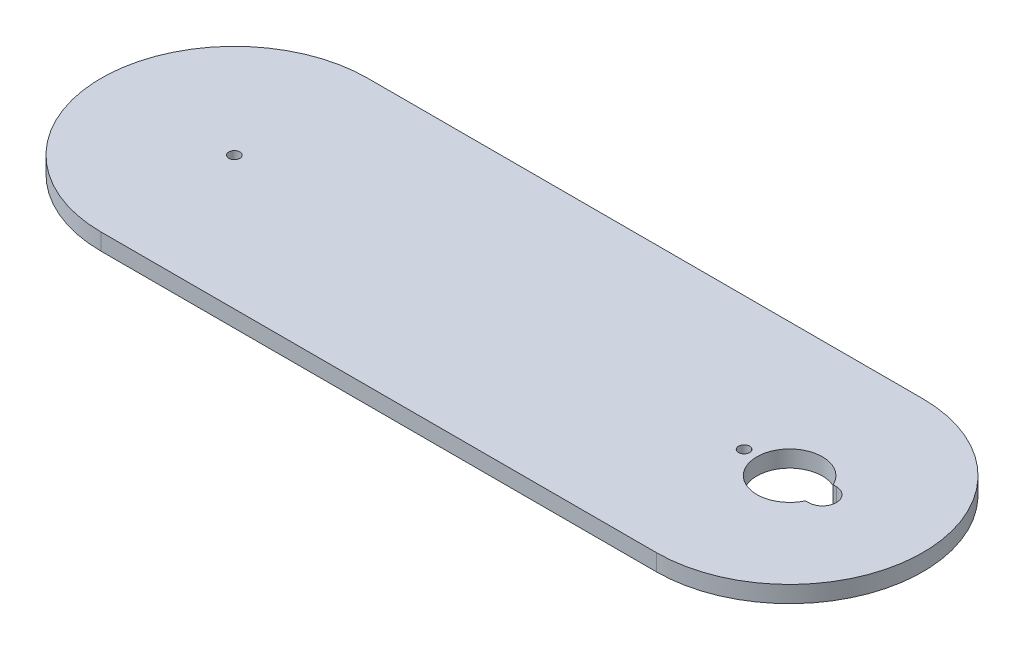
SolidWorks part; units mm, degrees
ref_plane "Front Plane" through (0, 0, 0) normal (0, 0, 1) x (1, 0, 0)
ref_plane "Top Plane" through (0, 0, 0) normal (0, 1, 0) x (1, 0, 0)
ref_plane "Right Plane" through (0, 0, 0) normal (1, 0, 0) x (0, 0, -1)
sketch "Sketch1" plane through (0, 0, 0) normal (0, 1, 0) x (1, 0, 0)
  line L0 (0, 24) -> (100, 24)
  line L2 (100, -24) -> (0, -24)
  arc A0 (0, 24) -> (0, -24) centre (0, 0) ccw
  arc A1 (100, 24) -> (100, -24) centre (100, 0) cw
  dimension "D1" = 48
  dimension "D4" = 24
  dimension "D2" = 48
  dimension "D3" = 100
extrude "Boss-Extrude1" add sketch "Sketch1" along normal blind 3
sketch "Sketch2" plane through (0, 3, 0) normal (0, 1, 0) x (1, 0, 0)
  circle A0 centre (0, 0) radius 1
  arc A1 (0, 24) -> (0, -24) centre (0, 0) ccw construction
  point P5 (0, 0)
  dimension "D1" = 2
extrude "Cut-Extrude1" cut sketch "Sketch2" against normal blind 3
sketch "Sketch3" plane through (0, 3, 0) normal (0, 1, 0) x (1, 0, 0)
  line L0 (105.3442, 2.5) -> (105.9042, 2.5)
  line L2 (105.9042, -2.5) -> (105.3442, -2.5)
  arc A0 (105.3442, 2.5) -> (105.3442, -2.5) centre (100, 0) ccw
  arc A1 (100, -24) -> (100, 24) centre (100, 0) ccw construction
  arc A2 (105.9042, 2.5) -> (105.9042, -2.5) centre (105.9042, 0) cw
  point P10 (0, 0)
  dimension "D1" = 11.8
  dimension "D2" = 2.5
  dimension "D3" = 0.56
extrude "Cut-Extrude2" cut sketch "Sketch3" against normal blind 3
sketch "Sketch4" plane through (0, 3, 0) normal (0, 1, 0) x (1, 0, 0)
  circle A0 centre (91.8, 0) radius 1
  arc A1 (105.3442, 2.5) -> (105.3442, -2.5) centre (100, 0) ccw construction
  arc A2 (100, -24) -> (100, 24) centre (100, 0) ccw construction
  point P2 (0, 0)
  point P6 (94.1, 0)
  point P10 (124, 0)
  dimension "D2" = 2
  dimension "D1" = 2.3
extrude "Cut-Extrude3" cut sketch "Sketch4" against normal blind 3
